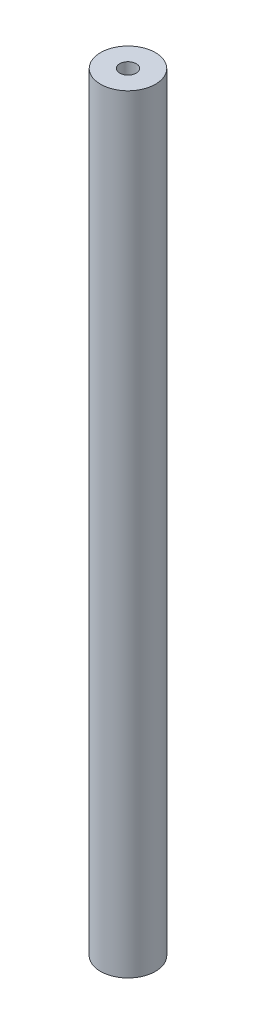
SolidWorks part; units mm, degrees
ref_plane "Front Plane" through (0, 0, 0) normal (0, 0, 1) x (1, 0, 0)
ref_plane "Top Plane" through (0, 0, 0) normal (0, 1, 0) x (1, 0, 0)
ref_plane "Right Plane" through (0, 0, 0) normal (1, 0, 0) x (0, 0, -1)
sketch "Sketch1" plane through (0, 0, 0) normal (0, 1, 0) x (1, 0, 0)
  circle A0 centre (0, 0) radius 5
  circle A1 centre (0, 0) radius 1.5
  dimension "D1" = 10
  dimension "D2" = 3
extrude "Boss-Extrude1" add sketch "Sketch1" along normal blind 140
